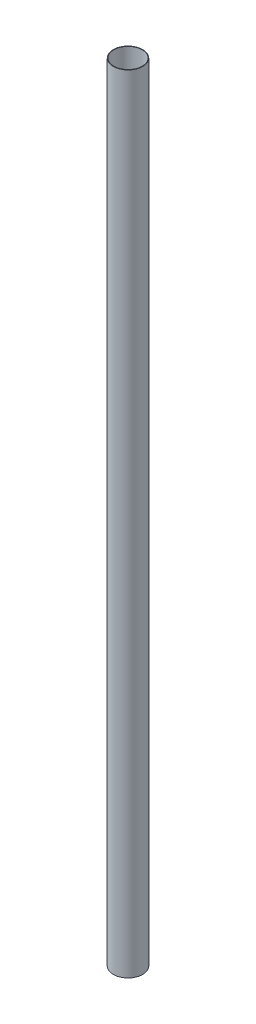
SolidWorks part; units mm, degrees
ref_plane "Front Plane" through (0, 0, 0) normal (0, 0, 1) x (1, 0, 0)
ref_plane "Top Plane" through (0, 0, 0) normal (0, 1, 0) x (1, 0, 0)
ref_plane "Right Plane" through (0, 0, 0) normal (1, 0, 0) x (0, 0, -1)
sketch "Sketch1" plane through (0, 0, 0) normal (0, 1, 0) x (1, 0, 0)
  circle A0 centre (0, 0) radius 15.5
extrude "Boss-Extrude1" add sketch "Sketch1" along normal blind 830
sketch "Sketch3" plane through (0, 830, 0) normal (0, 1, 0) x (1, 0, 0)
  circle A0 centre (0, 0) radius 15
extrude "Cut-Extrude2" cut sketch "Sketch3" against normal blind 931
